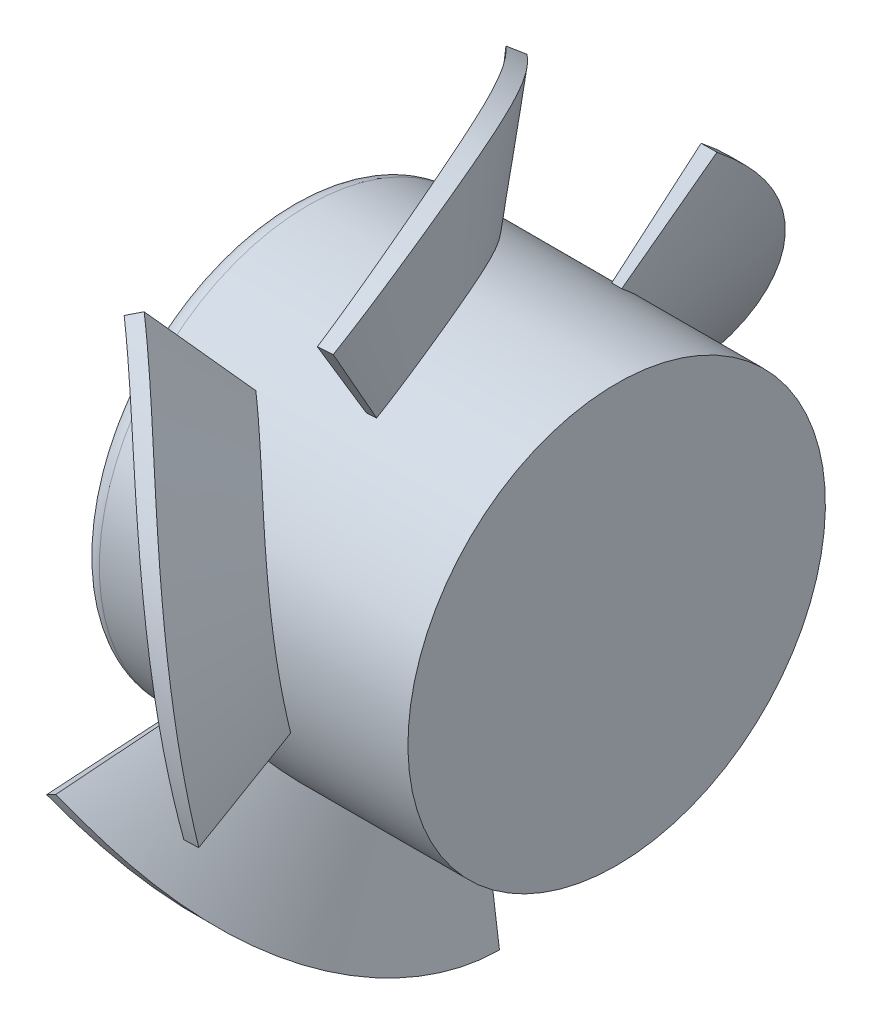
SolidWorks part; units mm, degrees
material "PW100:Mi:0:30:C1:0:1:2:Re:16:"
ref_plane "Front" through (0, 0, 0) normal (0, 0, 1) x (1, 0, 0)
ref_plane "Top" through (0, 0, 0) normal (0, 1, 0) x (1, 0, 0)
ref_plane "Right" through (0, 0, 0) normal (1, 0, 0) x (0, 0, -1)
sketch "Support-Front" plane through (0, 0, 0) normal (0, 0, 1) x (1, 0, 0)
  line L0 (-20, 0) -> (-2, 0) construction
  line L1 (-20, -11.5) -> (-20, 11.5)
  line L2 (-20, 11.5) -> (-2, 11.5)
  line L3 (-20, -11.5) -> (-2, -11.5)
  line L4 (-2, 11.5) -> (-2, -11.5)
  line L5 (-11, 11.5) -> (-11, -11.5) construction
  line L6 (-2, 11.5) -> (0, 11.5) construction
  line L7 (-2, -11.5) -> (0, -11.5) construction
  line L8 (0, 11.5) -> (0, -11.5) construction
  line L11 (-11, 11.5) -> (-11, 18) construction
  line L12 (-11, -11.5) -> (-11, -18) construction
  point P12 (0, 0)
  point P14 (-11, 0)
  dimension "Width" = 20
  dimension "Diam-Body" = 23
  dimension "Diam-Fan" = 36
  dimension "Dist-Fan" = 2
sketch "Support-Right" plane through (0, 0, 0) normal (1, 0, 0) x (0, 0, -1)
  circle A0 centre (0, 0) radius 18
sketch "Support-Fan-Blade-Top" plane through (0, 0, 0) normal (0, 1, 0) x (-1, 0, 0)
  line L0 (11, 0) -> (8.0107, 11.9893) construction
  line L1 (17.9096, -10.2438) -> (8.0107, 11.9893) construction
  line L2 (12.9601, 0.8727) -> (11, 0) construction
  line L4 (20, 0) -> (8.0107, 11.9893) construction
  line L5 (20, 0) -> (2, 0) construction
  line L6 (7.0132, 11.9195) -> (8.0107, 11.9893)
  line L7 (17.1902, -10.9385) -> (17.9096, -10.2438)
  arc A0 (8.0107, 11.9893) -> (17.9096, -10.2438) centre (43.5026, 14.4711) ccw
  arc A1 (7.0132, 11.9195) -> (17.1902, -10.9385) centre (43.5026, 14.4711) ccw
  dimension "Angle-Fan-Blade" = 66
  dimension "D1" = 10
  dimension "D3" = 45
  dimension "D2" = 1
ref_plane "Plane-Angle-Fan-Blade" through (-9.1802, 0, 4.0873) normal (-0.9135, 0, 0.4067) x (0.4067, 0, 0.9135)
ref_plane "Plane-Top-Fan-Blade" through (0, 18, 0) normal (0, 1, 0) x (-1, 0, 0)
sketch "Sketch-Blade-Bottom" plane through (0, 0, 0) normal (0, 1, 0) x (1, 0, 0)
  point P0 (-11, 0)
sketch "Sketch-Blade-Top" plane through (0, 18, 0) normal (0, 1, 0) x (-1, 0, 0)
  line L2 (8.0107, 11.9893) -> (7.0132, 11.9195)
  line L3 (17.1902, -10.9385) -> (17.9096, -10.2438)
  line L4 (8.0107, 11.9893) -> (7.0132, 11.9195)
  line L5 (17.1902, -10.9385) -> (17.9096, -10.2438)
  arc A3 (7.0132, 11.9195) -> (17.1902, -10.9385) centre (43.5026, 14.4711) ccw
  arc A4 (8.0107, 11.9893) -> (17.9096, -10.2438) centre (43.5026, 14.4711) ccw
  arc A5 (7.0132, 11.9195) -> (17.1902, -10.9385) centre (43.5026, 14.4711) ccw
  arc A6 (8.0107, 11.9893) -> (17.9096, -10.2438) centre (43.5026, 14.4711) ccw
  dimension "D1" = 0
sketch "Sketch5" plane through (0, 0, 0) normal (0, 0, 1) x (1, 0, 0)
  line L0 (-2, 11.5) -> (-2, -11.5) construction
  line L1 (-20, -11.5) -> (-20, 11.5) construction
  line L4 (-2, 11.5) -> (-2, 0)
  line L5 (-20, 0) -> (-20, 11.5)
  line L6 (-20, 0) -> (-2, 0)
  line L7 (-20, 11.5) -> (-2, 11.5) construction
  line L8 (-20, 0) -> (-2, 0) construction
  line L9 (-20, 0) -> (-2, 0) construction
  line L10 (-20, 11.5) -> (-2, 11.5)
revolve "Body" add sketch "Sketch5" angle 360 about L9
loft "Loft-Fan-Blade" add profiles "Sketch-Blade-Top", "Sketch-Blade-Bottom"
pattern_circular "CirPattern1" count 5 over 360 about axis through (-20, 0, 0) along (1, 0, 0) of "Loft-Fan-Blade"
sketch "Sketch-Cut-Blade" plane through (0, 0, 0) normal (1, 0, 0) x (0, 0, -1)
  circle A0 centre (0, 0) radius 18 construction
  circle A1 centre (0, 0) radius 18
extrude "Cut-Fan-Blade" cut sketch "Sketch-Cut-Blade" against normal through all flip side to cut
fillet "Cosmetic-Fillet" radius 1 1 edges at (-20, -11.5, 0)
equation "\"Angle-Blade@Plane-Angle-Fan-Blade\" = \"Angle-Fan-Blade@Support-Fan-Blade-Top\""
equation "\"Rad@Cosmetic-Fillet\" = \"Dist-Fan@Support-Front\" / 2"
